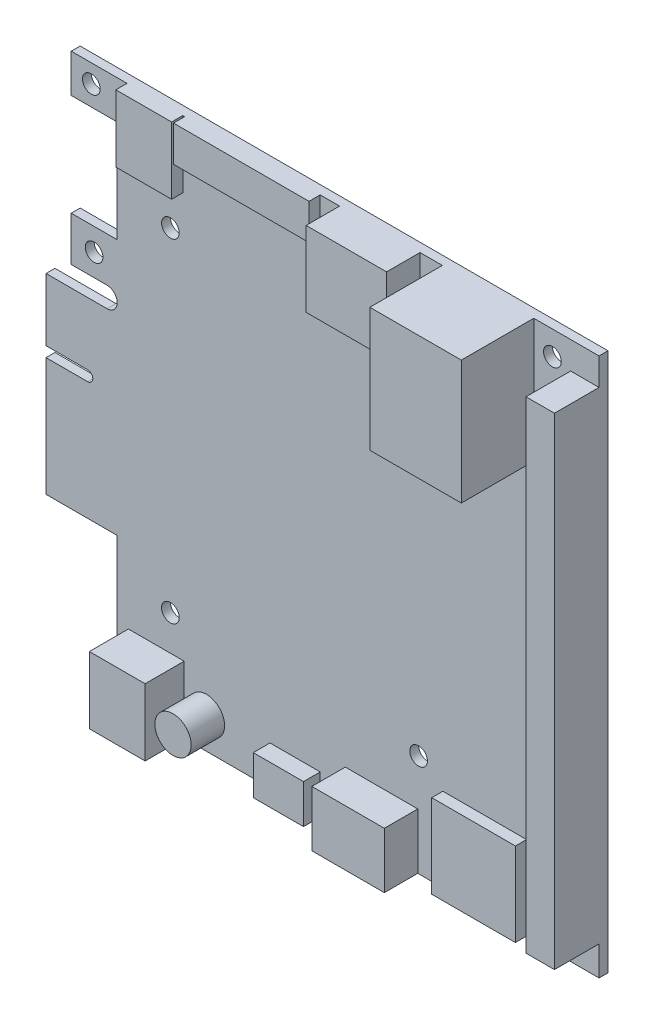
SolidWorks part; units mm, degrees
ref_plane "前视基准面" through (0, 0, 0) normal (0, 0, 1) x (1, 0, 0)
ref_plane "上视基准面" through (0, 0, 0) normal (0, 1, 0) x (1, 0, 0)
ref_plane "右视基准面" through (0, 0, 0) normal (1, 0, 0) x (0, 0, -1)
sketch "草图1" plane through (0, 0, 0) normal (0, 0, 1) x (1, 0, 0)
  line L0 (0, 4.42) -> (53.34, 4.42) construction
  line L1 (0, 0) -> (53.34, 0) construction
  line L2 (0, 0) -> (0, 68.58) construction
  line L3 (0, 68.58) -> (53.34, 68.58) construction
  line L4 (53.34, 0) -> (53.34, 68.58) construction
  line L5 (0, 64.16) -> (53.34, 64.16) construction
  line L6 (4.42, 68.58) -> (4.42, 0) construction
  line L7 (48.92, 68.58) -> (48.92, 0) construction
  line L8 (-13.36, 82.72) -> (-13.36, -13.88) construction
  line L9 (-17.88, 82.72) -> (81.28, 82.72) construction
  line L10 (-17.88, 82.72) -> (-17.88, -13.88) construction
  line L11 (-17.88, -13.88) -> (81.28, -13.88) construction
  line L12 (81.28, 82.72) -> (81.28, -13.88) construction
  line L13 (81.28, 82.72) -> (-13.36, 82.72)
  line L18 (-13.36, 75.84) -> (-5.19, 75.84) construction
  line L19 (-13.36, 75.84) -> (-13.36, 57.56) construction
  line L20 (-13.36, 57.56) -> (-5.19, 57.56) construction
  line L21 (-5.19, 75.84) -> (-5.19, 57.56) construction
  line L22 (-13.36, 49.59) -> (-6.94, 49.59) construction
  line L23 (-13.36, 49.59) -> (-13.36, 45.94) construction
  line L24 (-13.36, 45.94) -> (-6.94, 45.94) construction
  line L25 (-6.94, 49.59) -> (-6.94, 45.94) construction
  line L26 (-13.36, 45.94) -> (-17.88, 45.94) construction
  line L27 (-13.36, 45.94) -> (-13.36, 34.72) construction
  line L28 (-13.36, 34.72) -> (-17.88, 34.72) construction
  line L29 (-17.88, 45.94) -> (-17.88, 34.72) construction
  line L30 (-13.36, 34.72) -> (-10.42, 34.72) construction
  line L31 (-13.36, 34.72) -> (-13.36, 32.87) construction
  line L32 (-13.36, 32.87) -> (-10.42, 32.87) construction
  line L33 (-10.42, 34.72) -> (-10.42, 32.87) construction
  line L34 (-13.36, 32.87) -> (-17.88, 32.87) construction
  line L35 (-13.36, 32.87) -> (-13.36, 11.64) construction
  line L36 (-13.36, 11.64) -> (-17.88, 11.64) construction
  line L37 (-17.88, 32.87) -> (-17.88, 11.64) construction
  line L38 (-13.36, 11.64) -> (-5.11, 11.64) construction
  line L39 (-13.36, 11.64) -> (-13.36, -13.88) construction
  line L40 (-13.36, -13.88) -> (-5.11, -13.88) construction
  line L41 (-5.11, 11.64) -> (-5.11, -13.88) construction
  line L42 (-13.36, 82.72) -> (-13.36, 75.84)
  line L43 (-13.36, 75.84) -> (-5.19, 75.84)
  line L44 (-5.19, 75.84) -> (-5.19, 57.56)
  line L45 (-5.19, 57.56) -> (-13.36, 57.56)
  line L46 (-13.36, 57.56) -> (-13.36, 49.59)
  line L47 (-13.36, 49.59) -> (-6.94, 49.59)
  line L48 (-6.94, 45.94) -> (-17.88, 45.94)
  line L49 (-17.88, 45.94) -> (-17.88, 34.72)
  line L50 (-17.88, 34.72) -> (-10.42, 34.72)
  line L51 (-10.42, 32.87) -> (-17.88, 32.87)
  line L52 (-17.88, 32.87) -> (-17.88, 11.64)
  line L53 (-17.88, 11.64) -> (-5.11, 11.64)
  line L54 (-5.11, 11.64) -> (-5.11, -13.88)
  line L55 (-5.11, -13.88) -> (81.28, -13.88)
  line L56 (81.28, -13.88) -> (81.28, 82.72)
  circle A0 centre (48.92, 64.16) radius 1.585
  circle A1 centre (4.42, 64.16) radius 1.585
  circle A2 centre (4.42, 4.42) radius 1.585
  circle A3 centre (48.92, 4.42) radius 1.585
  circle A5 centre (72.92, -9.58) radius 1.585
  circle A6 centre (72.92, 78.42) radius 1.585
  circle A7 centre (-6.94, 47.765) radius 1.825 construction
  circle A8 centre (-10.42, 33.795) radius 0.925 construction
  arc A9 (-6.94, 45.94) -> (-6.94, 49.59) centre (-6.94, 47.765) ccw
  arc A10 (-10.42, 32.87) -> (-10.42, 34.72) centre (-10.42, 33.795) ccw
  circle A11 centre (-9.76, 79.42) radius 1.585
  circle A12 centre (-9.26, 53.56) radius 1.585
  dimension "D7" = 3.17
  dimension "D8" = 3.17
  dimension "D9" = 3.17
  dimension "D10" = 3.17
  dimension "D15" = 18.28
  dimension "D18" = 3.17
  dimension "D21" = 3.17
  dimension "D24" = 3.65
  dimension "D36" = 3.17
  dimension "D39" = 3.17
  dimension "D1" = 68.58
  dimension "D2" = 53.34
  dimension "D3" = 4.42
  dimension "D4" = 4.42
  dimension "D5" = 4.42
  dimension "D6" = 4.42
  dimension "D11" = 99.16
  dimension "D12" = 96.6
  dimension "D13" = 94.64
  dimension "D14" = 6.88
  dimension "D16" = 68.5
  dimension "D17" = 14
  dimension "D19" = 74
  dimension "D20" = 68.5
  dimension "D22" = 8.17
  dimension "D23" = 6.42
  dimension "D25" = 22.3
  dimension "D26" = 18.3
  dimension "D27" = 7.97
  dimension "D29" = 11.22
  dimension "D30" = 2.94
  dimension "D31" = 1.85
  dimension "D32" = 21.23
  dimension "D33" = 8.25
  dimension "D34" = 3.6
  dimension "D35" = 3.3
  dimension "D37" = 4.1
  dimension "D38" = 4
extrude "凸台-拉伸1" add sketch "草图1" along normal blind 1.6
sketch "草图2" plane through (0, 0, 1.6) normal (0, 0, 1) x (1, 0, 0)
  line L0 (81.28, -13.88) -> (81.28, 82.72) construction
  line L1 (81.28, 77.82) -> (76.18, 77.82)
  line L2 (81.28, 77.82) -> (81.28, -8.58)
  line L3 (81.28, -8.58) -> (76.18, -8.58)
  line L4 (76.18, 77.82) -> (76.18, -8.58)
  line L5 (81.28, 82.72) -> (-13.36, 82.72) construction
  line L6 (-5.11, -13.88) -> (81.28, -13.88) construction
  dimension "D1" = 4.9
  dimension "D2" = 5.3
  dimension "D3" = 5.1
extrude "凸台-拉伸2" add sketch "草图2" along normal blind 8
sketch "草图3" plane through (0, 0, 1.6) normal (0, 0, 1) x (1, 0, 0)
  line L0 (81.28, 82.72) -> (-13.36, 82.72) construction
  line L1 (69.58, 82.72) -> (53.18, 82.72)
  line L2 (69.58, 82.72) -> (69.58, 60.52)
  line L3 (69.58, 60.52) -> (53.18, 60.52)
  line L4 (53.18, 82.72) -> (53.18, 60.52)
  line L5 (81.28, 77.82) -> (81.28, 82.72) construction
  dimension "D1" = 11.7
  dimension "D2" = 16.4
  dimension "D3" = 22.2
extrude "凸台-拉伸3" add sketch "草图3" along normal blind 13
sketch "草图4" plane through (0, 0, 1.6) normal (0, 0, 1) x (1, 0, 0)
  line L0 (53.18, 82.72) -> (-13.36, 82.72) construction
  line L1 (49.18, 82.72) -> (34.76, 82.72)
  line L2 (49.18, 82.72) -> (49.18, 69.22)
  line L3 (49.18, 69.22) -> (34.76, 69.22)
  line L4 (34.76, 82.72) -> (34.76, 69.22)
  line L5 (81.28, 77.82) -> (81.28, 82.72) construction
  dimension "D1" = 14.42
  dimension "D2" = 13.5
  dimension "D3" = 32.1
extrude "凸台-拉伸4" add sketch "草图4" along normal blind 6
sketch "草图5" plane through (0, 0, 1.6) normal (0, 0, 1) x (1, 0, 0)
  line L0 (34.76, 82.72) -> (-13.36, 82.72) construction
  line L1 (6.98, 82.72) -> (31.28, 82.72)
  line L2 (6.98, 82.72) -> (6.98, 76.32)
  line L3 (6.98, 76.32) -> (31.28, 76.32)
  line L4 (31.28, 82.72) -> (31.28, 76.32)
  line L5 (81.28, 77.82) -> (81.28, 82.72) construction
  dimension "D1" = 50
  dimension "D2" = 24.3
  dimension "D3" = 6.4
extrude "凸台-拉伸5" add sketch "草图5" along normal blind 2
sketch "草图6" plane through (0, 0, 1.6) normal (0, 0, 1) x (1, 0, 0)
  line L0 (6.98, 82.72) -> (-13.36, 82.72) construction
  line L1 (-3.36, 82.72) -> (6.64, 82.72)
  line L2 (-3.36, 82.72) -> (-3.36, 70.72)
  line L3 (-3.36, 70.72) -> (6.64, 70.72)
  line L4 (6.64, 82.72) -> (6.64, 70.72)
  line L5 (-13.36, 82.72) -> (-13.36, 75.84) construction
  dimension "D1" = 10
  dimension "D2" = 10
  dimension "D3" = 12
extrude "凸台-拉伸6" add sketch "草图6" along normal blind 2
sketch "草图7" plane through (0, 0, 1.6) normal (0, 0, 1) x (1, 0, 0)
  line L0 (-5.11, -13.88) -> (81.28, -13.88) construction
  line L1 (68.28, -13.88) -> (53.28, -13.88)
  line L2 (68.28, -13.88) -> (68.28, 1.12)
  line L3 (68.28, 1.12) -> (53.28, 1.12)
  line L4 (53.28, -13.88) -> (53.28, 1.12)
  line L5 (81.28, -13.88) -> (81.28, -8.58) construction
  dimension "D1" = 13
  dimension "D2" = 15
  dimension "D3" = 15
extrude "凸台-拉伸7" add sketch "草图7" along normal blind 2
sketch "草图8" plane through (0, 0, 1.6) normal (0, 0, 1) x (1, 0, 0)
  line L0 (-5.11, -13.88) -> (53.28, -13.88) construction
  line L1 (48.78, -13.88) -> (35.78, -13.88)
  line L2 (48.78, -13.88) -> (48.78, -3.88)
  line L3 (48.78, -3.88) -> (35.78, -3.88)
  line L4 (35.78, -13.88) -> (35.78, -3.88)
  line L5 (81.28, -13.88) -> (81.28, -8.58) construction
  dimension "D1" = 32.5
  dimension "D2" = 13
  dimension "D3" = 10
extrude "凸台-拉伸8" add sketch "草图8" along normal blind 6
sketch "草图9" plane through (0, 0, 1.6) normal (0, 0, 1) x (1, 0, 0)
  line L0 (-5.11, -13.88) -> (35.78, -13.88) construction
  line L1 (31.28, -13.88) -> (22.28, -13.88)
  line L2 (31.28, -13.88) -> (31.28, -6.88)
  line L3 (31.28, -6.88) -> (22.28, -6.88)
  line L4 (22.28, -13.88) -> (22.28, -6.88)
  line L5 (81.28, -8.58) -> (81.28, 77.82) construction
  dimension "D1" = 9
  dimension "D2" = 50
  dimension "D3" = 7
extrude "凸台-拉伸9" add sketch "草图9" along normal blind 3
sketch "草图10" plane through (0, 0, 1.6) normal (0, 0, 1) x (1, 0, 0)
  line L0 (-5.11, -13.88) -> (22.28, -13.88) construction
  line L1 (-3.11, -13.88) -> (6.89, -13.88)
  line L2 (-3.11, -13.88) -> (-3.11, -1.88)
  line L3 (-3.11, -1.88) -> (6.89, -1.88)
  line L4 (6.89, -13.88) -> (6.89, -1.88)
  line L5 (-5.11, 11.64) -> (-5.11, -13.88) construction
  dimension "D1" = 2
  dimension "D2" = 10
  dimension "D3" = 12
extrude "凸台-拉伸10" add sketch "草图10" along normal blind 7
sketch "草图11" plane through (0, 0, 1.6) normal (0, 0, 1) x (1, 0, 0)
  line L0 (-5.11, 11.64) -> (-5.11, -13.88) construction
  line L1 (6.89, -13.88) -> (22.28, -13.88) construction
  circle A0 centre (10.89, -8.28) radius 3.25
  dimension "D3" = 6.5
  dimension "D1" = 16
  dimension "D2" = 5.6
extrude "凸台-拉伸11" add sketch "草图11" along normal blind 6
sketch "草图12" plane through (0, 0, 0) normal (0, 0, -1) x (-1, 0, 0)
  line L0 (-81.28, -13.88) -> (-81.28, 82.72) construction
  line L1 (-69.18, 10.12) -> (-54.48, 10.12)
  line L2 (-69.18, 10.12) -> (-69.18, 14.72)
  line L3 (-69.18, 14.72) -> (-54.48, 14.72)
  line L4 (-54.48, 10.12) -> (-54.48, 14.72)
  line L5 (5.11, -13.88) -> (-81.28, -13.88) construction
  line L7 (-12.28, 37.02) -> (-7.28, 37.02)
  line L8 (-12.28, 37.02) -> (-12.28, 13.12)
  line L9 (-12.28, 13.12) -> (-7.28, 13.12)
  line L10 (-7.28, 37.02) -> (-7.28, 13.12)
  dimension "D1" = 12.1
  dimension "D2" = 24
  dimension "D3" = 14.7
  dimension "D4" = 4.6
  dimension "D5" = 69
  dimension "D6" = 27
  dimension "D7" = 5
  dimension "D8" = 23.9
extrude "凸台-拉伸12" add sketch "草图12" along normal blind 2
sketch "草图14" plane through (0, 0, 0) normal (0, 0, -1) x (-1, 0, 0)
  line L0 (5.11, 11.64) -> (5.11, -13.88) construction
  line L1 (-7.89, -6.88) -> (-12.89, -6.88)
  line L2 (-7.89, -6.88) -> (-7.89, -10.88)
  line L3 (-7.89, -10.88) -> (-12.89, -10.88)
  line L4 (-12.89, -6.88) -> (-12.89, -10.88)
  line L5 (-21.89, 0.12) -> (-19.89, 0.12)
  line L6 (-21.89, 0.12) -> (-21.89, -3.88)
  line L7 (-21.89, -3.88) -> (-19.89, -3.88)
  line L8 (-19.89, 0.12) -> (-19.89, -3.88)
  line L9 (5.11, -13.88) -> (-81.28, -13.88) construction
  dimension "D1" = 13
  dimension "D2" = 3
  dimension "D3" = 5
  dimension "D4" = 4
  dimension "D5" = 25
  dimension "D6" = 10
  dimension "D7" = 2
  dimension "D8" = 4
extrude "凸台-拉伸13" add sketch "草图14" along normal blind 2
